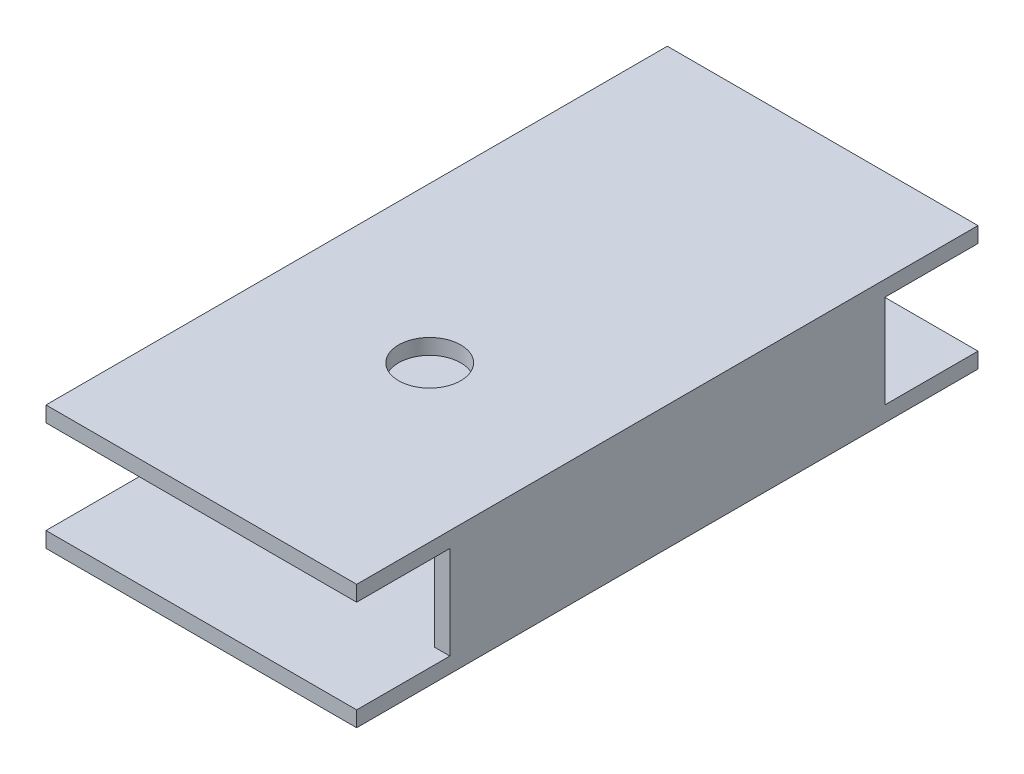
SolidWorks part; units mm, degrees
ref_plane "Front Plane" through (0, 0, 0) normal (0, 0, 1) x (1, 0, 0)
ref_plane "Top Plane" through (0, 0, 0) normal (0, 1, 0) x (1, 0, 0)
ref_plane "Right Plane" through (0, 0, 0) normal (1, 0, 0) x (0, 0, -1)
sketch "Sketch1" plane through (0, 0, 0) normal (0, 0, 1) x (1, 0, 0)
  line L1 (0, 0) -> (63.5, 0)
  line L2 (0, 0) -> (0, 25.4)
  line L3 (0, 25.4) -> (63.5, 25.4)
  line L4 (63.5, 0) -> (63.5, 25.4)
  dimension "D1" = 25.4
  dimension "D2" = 63.5
extrude "Extrude-Thin1" add sketch "Sketch1" along normal blind 127 thin thin type one direction reverse wall 3.175
sketch "Sketch2" plane through (63.5, 0, 0) normal (1, 0, 0) x (0, 0, -1)
  line L0 (0, 0) -> (0, 25.4) construction
  line L1 (0, 22.225) -> (-19.05, 22.225)
  line L2 (0, 22.225) -> (0, 3.175)
  line L3 (0, 3.175) -> (-19.05, 3.175)
  line L4 (-19.05, 22.225) -> (-19.05, 3.175)
  line L5 (-127, 25.4) -> (0, 25.4) construction
  line L6 (-127, 0) -> (0, 0) construction
  dimension "D1" = 3.175
  dimension "D2" = 3.175
  dimension "D3" = 19.05
extrude "Cut-Extrude1" cut sketch "Sketch2" against normal through all
sketch "Sketch3" plane through (63.5, 0, 0) normal (1, 0, 0) x (0, 0, -1)
  line L0 (-127, 0) -> (-127, 25.4) construction
  line L1 (-127, 22.225) -> (-107.95, 22.225)
  line L2 (-127, 22.225) -> (-127, 3.175)
  line L3 (-127, 3.175) -> (-107.95, 3.175)
  line L4 (-107.95, 22.225) -> (-107.95, 3.175)
  line L5 (-127, 25.4) -> (0, 25.4) construction
  line L6 (-127, 0) -> (0, 0) construction
  dimension "D1" = 3.175
  dimension "D2" = 3.175
  dimension "D3" = 19.05
extrude "Cut-Extrude2" cut sketch "Sketch3" against normal through all
sketch "Sketch4" plane through (0, 25.4, 0) normal (0, 1, 0) x (1, 0, 0)
  line L0 (63.5, -127) -> (0, -127) construction
  circle A0 centre (31.75, -80.3275) radius 6.35
  point P3 (31.75, 0)
  point P11 (36.7899, -63.5)
  dimension "D2" = 46.6725
  dimension "D1" = 12.7
extrude "Cut-Extrude3" cut sketch "Sketch4" against normal through all
